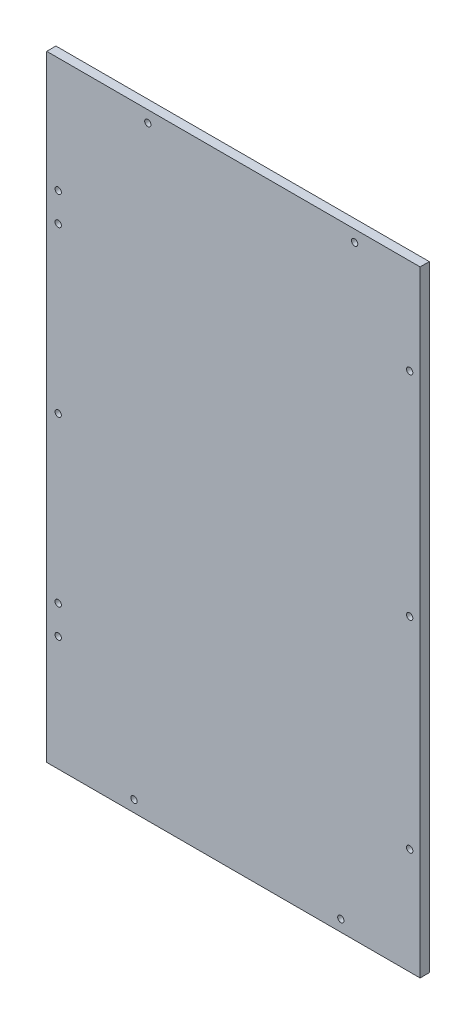
SolidWorks part; units mm, degrees
ref_plane "Front Plane" through (0, 0, 0) normal (0, 0, 1) x (1, 0, 0)
ref_plane "Top Plane" through (0, 0, 0) normal (0, 1, 0) x (1, 0, 0)
ref_plane "Right Plane" through (0, 0, 0) normal (1, 0, 0) x (0, 0, -1)
sketch "Sketch1" plane through (0, 0, 0) normal (0, 0, 1) x (1, 0, 0)
  line L0 (57, 268) -> (57, -268)
  line L1 (-268, 268) -> (57, 268)
  line L2 (-268, 268) -> (-268, -268)
  line L3 (-268, -268) -> (57, -268)
  line L4 (47.94, 258) -> (47.94, -258) construction
  line L5 (-268, 268) -> (57, -57) construction
  line L6 (-268, -268) -> (57, 57) construction
  line L7 (-258, 258) -> (57, 258) construction
  line L8 (-258, 258) -> (-258, -258) construction
  line L9 (-258, -258) -> (57, -258) construction
  circle A0 centre (0, 258) radius 2.75
  circle A1 centre (-180, 258) radius 2.75
  circle A3 centre (47.94, 0) radius 2.75
  circle A4 centre (47.94, 185.0319) radius 2.75
  circle A5 centre (47.94, -175.4533) radius 2.75
  circle A6 centre (-12.0095, -258) radius 2.75
  circle A8 centre (-192.0095, -258) radius 2.75
  circle A9 centre (-257.9999, 0) radius 2.75
  circle A10 centre (-257.9999, -167.9905) radius 2.75
  circle A11 centre (-257.9999, 168.0095) radius 2.75
  circle A12 centre (-257.9999, 143.0095) radius 2.75
  circle A13 centre (-257.9999, -142.9905) radius 2.75
  point P0 (0, 0)
  point P16 (0, 258)
  point P41 (-6.0047, 6.0048)
  dimension "D3" = 180
  dimension "D1" = 536
  dimension "D2" = 325
  dimension "D7" = 311
  dimension "D5" = 25
  dimension "D8" = 25
extrude "Boss-Extrude1" add sketch "Sketch1" along normal blind 8
